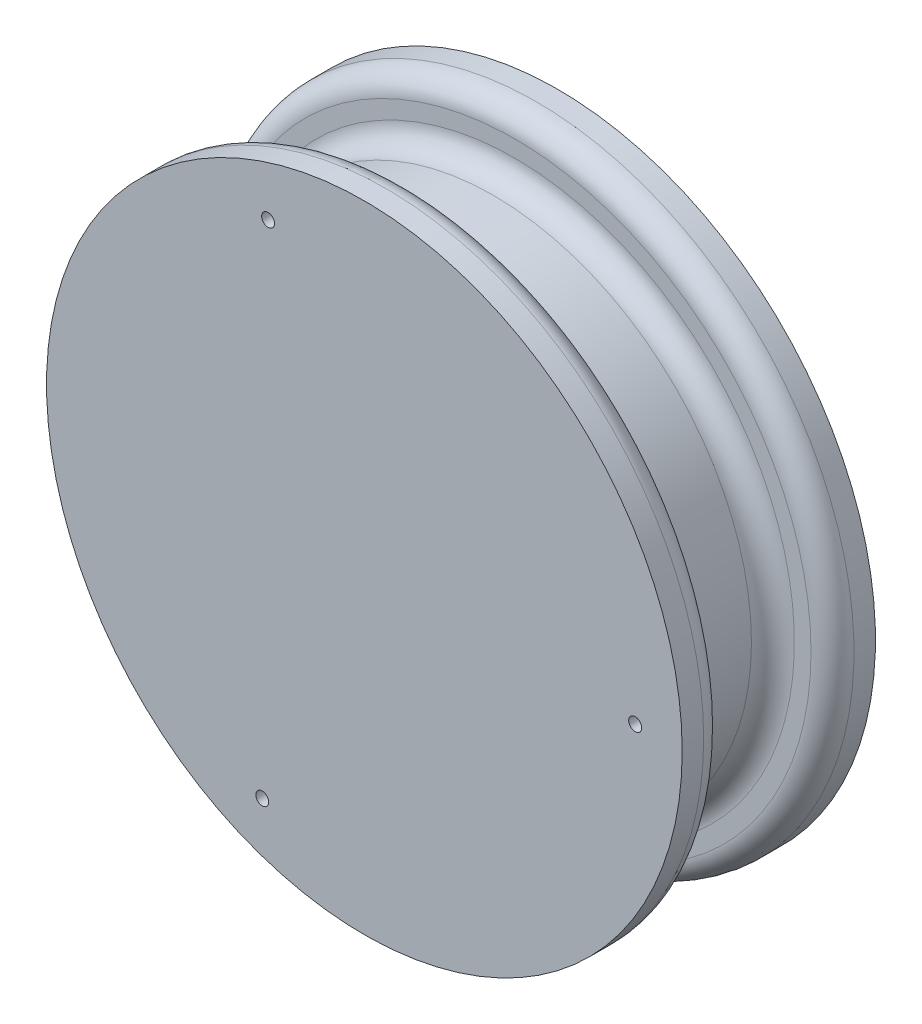
SolidWorks part; units mm, degrees
ref_plane "Front Plane" through (0, 0, 0) normal (0, 0, 1) x (1, 0, 0)
ref_plane "Top Plane" through (0, 0, 0) normal (0, 1, 0) x (1, 0, 0)
ref_plane "Right Plane" through (0, 0, 0) normal (1, 0, 0) x (0, 0, -1)
sketch "Sketch1" plane through (0, 0, 0) normal (0, 0, 1) x (1, 0, 0)
  circle A0 centre (0, 0) radius 14.7992
extrude "Boss-Extrude1" add sketch "Sketch1" along normal blind 2
sketch "Sketch2" plane through (0, 0, 0) normal (0, 0, -1) x (-1, 0, 0)
  circle A0 centre (0, 0) radius 12.0234
extrude "Boss-Extrude2" add sketch "Sketch2" along normal blind 5 contours A0
sketch "Sketch3" plane through (0, 0, -5) normal (0, 0, -1) x (-1, 0, 0)
  circle A0 centre (0, 0) radius 14.7986
extrude "Boss-Extrude3" add sketch "Sketch3" along normal blind 2
sketch "Sketch4" plane through (0, 0, -7) normal (0, 0, -1) x (-1, 0, 0)
  circle A0 centre (0, 0) radius 6.0855
extrude "Boss-Extrude5" add sketch "Sketch4" along normal blind 3.8 contours A0
fillet "Fillet5" radius 1 1 edges at (14.7992, 0, 0)
fillet "Fillet6" radius 0.5 1 edges at (-12.0234, 0, 0)
sketch "Sketch5" plane through (0, 0, -10.8) normal (0, 0, -1) x (-1, 0, 0)
  line L0 (0, 0) -> (0, 2.3)
  circle A0 centre (0, 0) radius 3.4
sketch "Sketch6" plane through (0, 0, -10.8) normal (0, 0, -1) x (-1, 0, 0)
  line L0 (0, 0) -> (0, -2.3)
sketch "Sketch7" plane through (0, 0, -10.8) normal (0, 0, -1) x (-1, 0, 0)
  line L0 (0, -2.3) -> (-2.504, -2.3)
  line L1 (0, -2.3) -> (2.504, -2.3)
  line L2 (0, 2.3) -> (-2.504, 2.3)
  line L3 (0, 2.3) -> (2.504, 2.3)
  circle A0 centre (0, 0) radius 3.4 construction
  arc A1 (-2.504, -2.3) -> (-2.504, 2.3) centre (0, 0) cw
  arc A2 (2.504, -2.3) -> (2.504, 2.3) centre (0, 0) ccw
extrude "Cut-Extrude1" cut sketch "Sketch7" against normal blind 8.3 contours L0 A1 L2 L3 A2 L1
sketch "Sketch8" plane through (0, 0, 2) normal (0, 0, 1) x (1, 0, 0)
  circle A0 centre (0, 0) radius 12.6108
  circle A1 centre (12.6108, 0) radius 0.3025
  circle A2 centre (-4.4843, 11.7865) radius 0.3
  circle A3 centre (-4.7557, -11.6797) radius 0.3
extrude "Cut-Extrude3" cut sketch "Sketch8" against normal blind 2.3 contours A1 | A2 | A3
fillet "Fillet7" radius 1 1 edges at (-12.0234, 0, -5)
fillet "Fillet8" radius 1 1 edges at (-14.7986, 0, -5)
